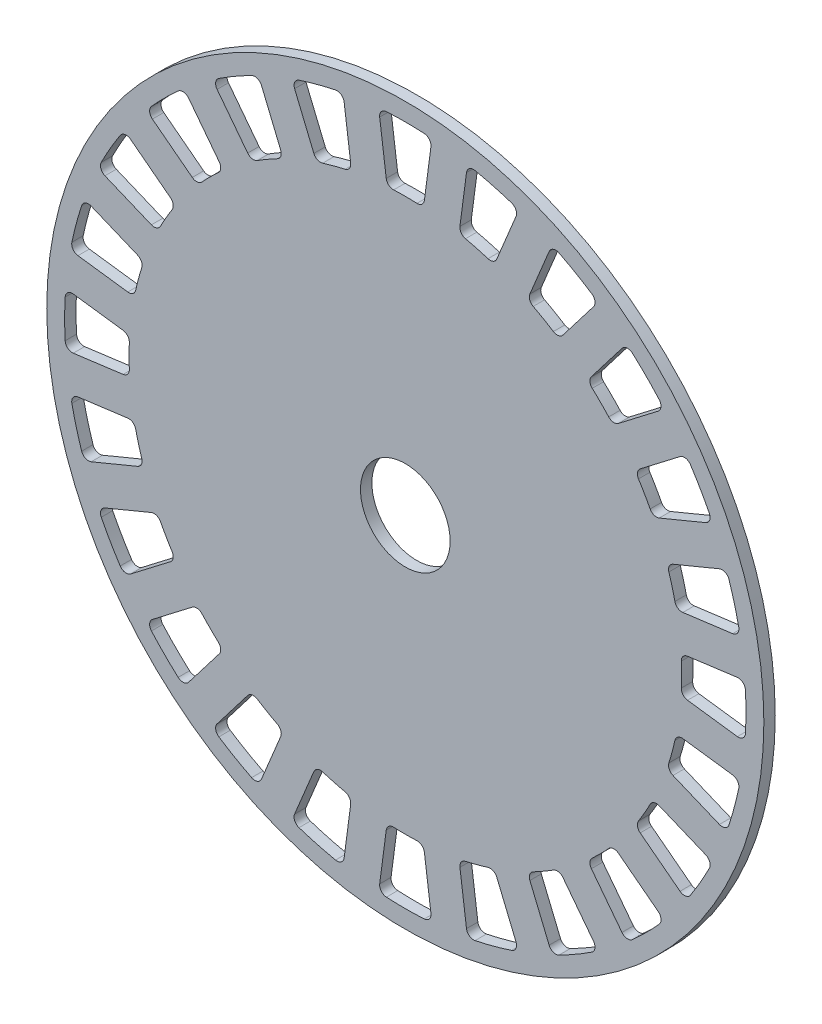
SolidWorks part; units mm, degrees
material "6061-T6 (SS)"
ref_plane "Front Plane" through (0, 0, 0) normal (0, 0, 1) x (1, 0, 0)
ref_plane "Top Plane" through (0, 0, 0) normal (0, 1, 0) x (1, 0, 0)
ref_plane "Right Plane" through (0, 0, 0) normal (1, 0, 0) x (0, 0, -1)
sketch "Sketch1" plane through (0, 0, 0) normal (0, 0, 1) x (1, 0, 0)
  circle A0 centre (0, 0) radius 100 construction
  circle A1 centre (0, 0) radius 100
  circle A2 centre (0, 0) radius 12.5 construction
  circle A3 centre (0, 0) radius 12.5
extrude "Plate Extrude" add sketch "Sketch1" along normal up to vertex (3.175 mm away)
sketch "Sketch2" plane through (0, 0, 3.175) normal (0, 0, 1) x (1, 0, 0)
  line L0 (0, 0) -> (13.0526, 99.1445) construction
  line L1 (0, 0) -> (-13.0526, 99.1445) construction
  line L2 (0, 0) -> (0, 100) construction
  line L4 (-6.5826, 50) -> (6.5826, 50) construction
  line L5 (5.077, 76.8699) -> (7.4264, 94.7159)
  line L6 (-5.077, 76.8699) -> (-7.4264, 94.7159)
  line L7 (6.2517, 85.7929) -> (11.2089, 85.1402) construction
  line L8 (-6.2517, 85.7929) -> (-11.2089, 85.1402) construction
  line L9 (7.4264, 94.7159) -> (8.0791, 99.6731) construction
  circle A0 centre (0, 0) radius 100 construction
  arc A1 (-13.0526, 99.1445) -> (13.0526, 99.1445) centre (0, 0) cw construction
  arc A2 (-7.4264, 94.7159) -> (7.4264, 94.7159) centre (0, 0) cw
  arc A3 (-5.077, 76.8699) -> (5.077, 76.8699) centre (0, 0) cw
  point P9 (0, 50)
  dimension "D1" = 15
  dimension "D2" = 5
  dimension "D3" = 18
extrude "Coil Mounting Cut" cut sketch "Sketch2" against normal through all
fillet "Coil Mounting Fillet" radius 2 4 edges at (5.077, 76.8699, 1.5875) (-5.077, 76.8699, 1.5875) (7.4264, 94.7159, 1.5875) (-7.4264, 94.7159, 1.5875)
pattern_circular "CirPattern1" count 24 over 360 about axis through (0, 0, 0) along (0, 0, 1) of "Coil Mounting Cut", "Coil Mounting Fillet"
equation "\"D1@Sketch2\"=360/24"
